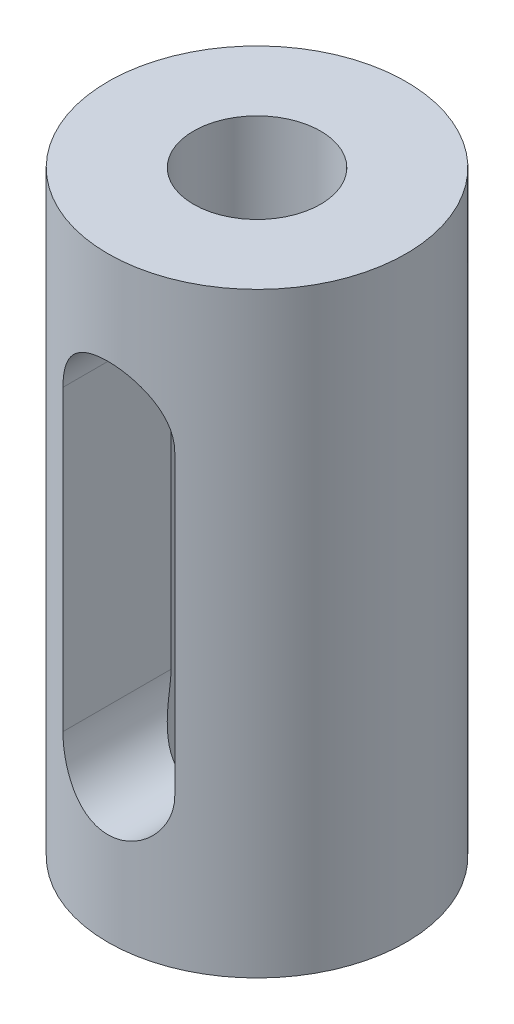
SolidWorks part; units mm, degrees
material "AISI 316 Stainless Steel Sheet (SS)"
ref_plane "Front Plane" through (0, 0, 0) normal (0, 0, 1) x (1, 0, 0)
ref_plane "Top Plane" through (0, 0, 0) normal (0, 1, 0) x (1, 0, 0)
ref_plane "Right Plane" through (0, 0, 0) normal (1, 0, 0) x (0, 0, -1)
sketch "Sketch1" plane through (0, 0, 0) normal (0, 1, 0) x (1, 0, 0)
  circle A0 centre (0, 0) radius 3.175
  dimension "D1" = 6.35
extrude "Boss-Extrude1" add sketch "Sketch1" along normal blind 12.7
hole_wizard "Tap Drill for #6-32 Tap1" positions "Sketch3" profile "Sketch2" hole size "#6-32" standard "ANSI Inch" end condition through all
sketch "Sketch3" plane through (0, 12.7, 0) normal (0, 1, 0) x (1, 0, 0)
  point P0 (0, 0)
sketch "Sketch2" plane through (0, 12.7, 0) normal (1, 0, 0) x (0, 0, 1)
  line L0 (0, 0) -> (0, 12.7)
  line L1 (0, 12.7) -> (1.3525, 12.7)
  line L2 (1.3525, 12.7) -> (1.3525, 0)
  line L5 (1.3525, 0) -> (0, 0)
  line L11 (0, -6.35) -> (0, 107.95) construction
  dimension "Thru Hole Dia." = 2.7051
  dimension "Thru Hole Depth" = 12.7
cosmetic thread "Cosmetic Thread1" parameters "D2"=3.5052
cosmetic thread "Cosmetic Thread2" parameters "D2"=3.5052
sketch "Sketch4" plane through (0, 0, 0) normal (0, 0, 1) x (1, 0, 0)
  line L0 (0, 9.525) -> (0, 3.175) construction
  line L1 (1.1906, 9.525) -> (1.1906, 3.175)
  line L2 (-1.1906, 9.525) -> (-1.1906, 3.175)
  line L3 (-3.175, 0) -> (3.175, 0) construction
  line L4 (3.175, 12.7) -> (-3.175, 12.7) construction
  arc A0 (1.1906, 9.525) -> (-1.1906, 9.525) centre (0, 9.525) ccw
  arc A1 (-1.1906, 3.175) -> (1.1906, 3.175) centre (0, 3.175) ccw
  point P3 (0, 6.35)
  dimension "D1" = 2.3813
  dimension "D2" = 3.175
  dimension "D3" = 3.175
extrude "Cut-Extrude1" cut sketch "Sketch4" against normal through all both and the other way through all
